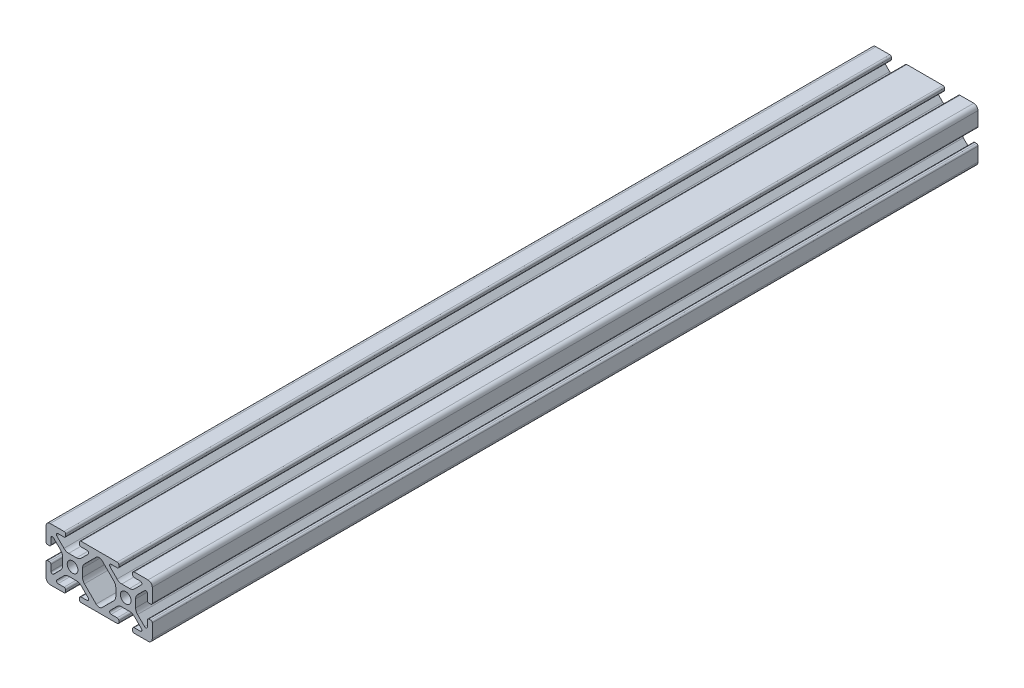
SolidWorks part; units mm, degrees
material "6063-T6"
ref_plane "Front" through (0, 0, 0) normal (0, 0, 1) x (1, 0, 0)
ref_plane "Top" through (0, 0, 0) normal (0, 1, 0) x (1, 0, 0)
ref_plane "Right" through (0, 0, 0) normal (1, 0, 0) x (0, 0, -1)
sketch "Sketch1" plane through (0, 0, 0) normal (0, 0, 1) x (1, 0, 0)
  line L0 (0, 0) -> (-63.6091, 63.6091) construction
  line L1 (0, 0) -> (53.0782, 0) construction
  line L2 (69.5504, 69.5504) -> (0, 0) construction
  line L3 (-7.4998, 9.0624) -> (-4.1172, 5.6797)
  line L4 (-10.668, 12.7) -> (10.668, 12.7) construction
  line L5 (-1.8721, 4.7498) -> (1.8721, 4.7498)
  line L6 (4.1172, 5.6797) -> (7.4998, 9.0624)
  line L7 (-3.302, 11.938) -> (-3.302, 11.1252)
  line L8 (-12.7, 10.668) -> (-12.7, -2.9469) construction
  line L9 (-10.668, 12.7) -> (-4.064, 12.7)
  line L10 (10.668, 12.7) -> (4.064, 12.7)
  line L11 (-6.961, 10.3632) -> (-4.064, 10.3632)
  line L12 (6.961, 10.3632) -> (4.064, 10.3632)
  line L13 (3.302, 11.938) -> (3.302, 11.1252)
  line L14 (-12.7, 10.668) -> (-12.7, 4.064)
  line L15 (-11.938, 3.302) -> (-11.1252, 3.302)
  line L16 (-10.3632, 4.064) -> (-10.3632, 6.961)
  line L17 (-9.0624, 7.4998) -> (-5.6797, 4.1172)
  line L18 (-4.7498, 1.8721) -> (-4.7498, -1.8721)
  line L19 (10.668, 12.7) -> (14.732, 12.7)
  line L20 (12.7, 12.7) -> (12.7, 19.2191) construction
  line L21 (4.7498, -1.8721) -> (4.7498, 1.8721)
  line L22 (5.6797, 4.1172) -> (11.2632, 9.7006)
  line L23 (5.6797, -4.1172) -> (11.2632, -9.7006)
  line L24 (10.668, -12.7) -> (14.732, -12.7)
  line L25 (-9.0624, -7.4998) -> (-5.6797, -4.1172)
  line L26 (-10.3632, -4.064) -> (-10.3632, -6.961)
  line L27 (-11.938, -3.302) -> (-11.1252, -3.302)
  line L28 (-12.7, -10.668) -> (-12.7, -4.064)
  line L29 (3.302, -11.938) -> (3.302, -11.1252)
  line L30 (6.961, -10.3632) -> (4.064, -10.3632)
  line L31 (-6.961, -10.3632) -> (-4.064, -10.3632)
  line L32 (10.668, -12.7) -> (4.064, -12.7)
  line L33 (-10.668, -12.7) -> (-4.064, -12.7)
  line L34 (-3.302, -11.938) -> (-3.302, -11.1252)
  line L35 (4.1172, -5.6797) -> (7.4998, -9.0624)
  line L36 (-1.8721, -4.7498) -> (1.8721, -4.7498)
  line L37 (-7.4998, -9.0624) -> (-4.1172, -5.6797)
  line L38 (32.8998, -9.0624) -> (29.5172, -5.6797)
  line L39 (27.2721, -4.7498) -> (23.5279, -4.7498)
  line L40 (21.2828, -5.6797) -> (17.9002, -9.0624)
  line L41 (28.702, -11.938) -> (28.702, -11.1252)
  line L42 (36.068, -12.7) -> (29.464, -12.7)
  line L43 (14.732, -12.7) -> (21.336, -12.7)
  line L44 (32.361, -10.3632) -> (29.464, -10.3632)
  line L45 (18.439, -10.3632) -> (21.336, -10.3632)
  line L46 (22.098, -11.938) -> (22.098, -11.1252)
  line L47 (38.1, -10.668) -> (38.1, -4.064)
  line L48 (37.338, -3.302) -> (36.5252, -3.302)
  line L49 (35.7632, -4.064) -> (35.7632, -6.961)
  line L50 (34.4624, -7.4998) -> (31.0797, -4.1172)
  line L51 (19.7203, -4.1172) -> (14.1368, -9.7006)
  line L52 (19.7203, 4.1172) -> (14.1368, 9.7006)
  line L53 (20.6502, -1.8721) -> (20.6502, 1.8721)
  line L54 (30.1498, 1.8721) -> (30.1498, -1.8721)
  line L55 (34.4624, 7.4998) -> (31.0797, 4.1172)
  line L56 (35.7632, 4.064) -> (35.7632, 6.961)
  line L57 (37.338, 3.302) -> (36.5252, 3.302)
  line L58 (38.1, 10.668) -> (38.1, 4.064)
  line L59 (22.098, 11.938) -> (22.098, 11.1252)
  line L60 (18.439, 10.3632) -> (21.336, 10.3632)
  line L61 (32.361, 10.3632) -> (29.464, 10.3632)
  line L62 (14.732, 12.7) -> (21.336, 12.7)
  line L63 (36.068, 12.7) -> (29.464, 12.7)
  line L64 (28.702, 11.938) -> (28.702, 11.1252)
  line L65 (21.2828, 5.6797) -> (17.9002, 9.0624)
  line L66 (27.2721, 4.7498) -> (23.5279, 4.7498)
  line L67 (32.8998, 9.0624) -> (29.5172, 5.6797)
  circle A0 centre (0, 0) radius 2.5527
  arc A1 (-10.668, 12.7) -> (-12.7, 10.668) centre (-10.668, 10.668) ccw
  arc A2 (14.1368, 9.7006) -> (11.2632, 9.7006) centre (12.7, 8.2638) ccw
  arc A3 (7.4998, 9.0624) -> (6.961, 10.3632) centre (6.961, 9.6012) ccw
  arc A4 (3.302, 11.1252) -> (4.064, 10.3632) centre (4.064, 11.1252) ccw
  arc A5 (3.302, 11.938) -> (4.064, 12.7) centre (4.064, 11.938) cw
  arc A6 (-3.302, 11.938) -> (-4.064, 12.7) centre (-4.064, 11.938) ccw
  arc A7 (-4.064, 10.3632) -> (-3.302, 11.1252) centre (-4.064, 11.1252) ccw
  arc A8 (-7.4998, 9.0624) -> (-6.961, 10.3632) centre (-6.961, 9.6012) cw
  arc A9 (1.8721, 4.7498) -> (4.1172, 5.6797) centre (1.8721, 7.9248) ccw
  arc A10 (-4.1172, 5.6797) -> (-1.8721, 4.7498) centre (-1.8721, 7.9248) ccw
  arc A11 (-5.6797, 4.1172) -> (-4.7498, 1.8721) centre (-7.9248, 1.8721) cw
  arc A12 (-12.7, 4.064) -> (-11.938, 3.302) centre (-11.938, 4.064) ccw
  arc A13 (-11.1252, 3.302) -> (-10.3632, 4.064) centre (-11.1252, 4.064) ccw
  arc A14 (-10.3632, 6.961) -> (-9.0624, 7.4998) centre (-9.6012, 6.961) cw
  arc A15 (4.7498, 1.8721) -> (5.6797, 4.1172) centre (7.9248, 1.8721) cw
  arc A16 (4.7498, -1.8721) -> (5.6797, -4.1172) centre (7.9248, -1.8721) ccw
  arc A17 (-10.3632, -6.961) -> (-9.0624, -7.4998) centre (-9.6012, -6.961) ccw
  arc A18 (-11.1252, -3.302) -> (-10.3632, -4.064) centre (-11.1252, -4.064) cw
  arc A19 (-12.7, -4.064) -> (-11.938, -3.302) centre (-11.938, -4.064) cw
  arc A20 (-5.6797, -4.1172) -> (-4.7498, -1.8721) centre (-7.9248, -1.8721) ccw
  arc A21 (-4.1172, -5.6797) -> (-1.8721, -4.7498) centre (-1.8721, -7.9248) cw
  arc A22 (1.8721, -4.7498) -> (4.1172, -5.6797) centre (1.8721, -7.9248) cw
  arc A23 (-7.4998, -9.0624) -> (-6.961, -10.3632) centre (-6.961, -9.6012) ccw
  arc A24 (-4.064, -10.3632) -> (-3.302, -11.1252) centre (-4.064, -11.1252) cw
  arc A25 (-3.302, -11.938) -> (-4.064, -12.7) centre (-4.064, -11.938) cw
  arc A26 (3.302, -11.938) -> (4.064, -12.7) centre (4.064, -11.938) ccw
  arc A27 (3.302, -11.1252) -> (4.064, -10.3632) centre (4.064, -11.1252) cw
  arc A28 (7.4998, -9.0624) -> (6.961, -10.3632) centre (6.961, -9.6012) cw
  arc A29 (14.1368, -9.7006) -> (11.2632, -9.7006) centre (12.7, -8.2638) cw
  arc A30 (-10.668, -12.7) -> (-12.7, -10.668) centre (-10.668, -10.668) cw
  arc A31 (36.068, -12.7) -> (38.1, -10.668) centre (36.068, -10.668) ccw
  arc A32 (17.9002, -9.0624) -> (18.439, -10.3632) centre (18.439, -9.6012) ccw
  arc A33 (22.098, -11.1252) -> (21.336, -10.3632) centre (21.336, -11.1252) ccw
  arc A34 (22.098, -11.938) -> (21.336, -12.7) centre (21.336, -11.938) cw
  arc A35 (28.702, -11.938) -> (29.464, -12.7) centre (29.464, -11.938) ccw
  arc A36 (29.464, -10.3632) -> (28.702, -11.1252) centre (29.464, -11.1252) ccw
  arc A37 (32.8998, -9.0624) -> (32.361, -10.3632) centre (32.361, -9.6012) cw
  arc A38 (23.5279, -4.7498) -> (21.2828, -5.6797) centre (23.5279, -7.9248) ccw
  arc A39 (29.5172, -5.6797) -> (27.2721, -4.7498) centre (27.2721, -7.9248) ccw
  arc A40 (31.0797, -4.1172) -> (30.1498, -1.8721) centre (33.3248, -1.8721) cw
  arc A41 (38.1, -4.064) -> (37.338, -3.302) centre (37.338, -4.064) ccw
  arc A42 (36.5252, -3.302) -> (35.7632, -4.064) centre (36.5252, -4.064) ccw
  arc A43 (35.7632, -6.961) -> (34.4624, -7.4998) centre (35.0012, -6.961) cw
  arc A44 (20.6502, -1.8721) -> (19.7203, -4.1172) centre (17.4752, -1.8721) cw
  arc A45 (20.6502, 1.8721) -> (19.7203, 4.1172) centre (17.4752, 1.8721) ccw
  arc A46 (35.7632, 6.961) -> (34.4624, 7.4998) centre (35.0012, 6.961) ccw
  arc A47 (36.5252, 3.302) -> (35.7632, 4.064) centre (36.5252, 4.064) cw
  arc A48 (38.1, 4.064) -> (37.338, 3.302) centre (37.338, 4.064) cw
  arc A49 (31.0797, 4.1172) -> (30.1498, 1.8721) centre (33.3248, 1.8721) ccw
  arc A50 (29.5172, 5.6797) -> (27.2721, 4.7498) centre (27.2721, 7.9248) cw
  arc A51 (23.5279, 4.7498) -> (21.2828, 5.6797) centre (23.5279, 7.9248) cw
  arc A52 (32.8998, 9.0624) -> (32.361, 10.3632) centre (32.361, 9.6012) ccw
  arc A53 (29.464, 10.3632) -> (28.702, 11.1252) centre (29.464, 11.1252) cw
  arc A54 (28.702, 11.938) -> (29.464, 12.7) centre (29.464, 11.938) cw
  arc A55 (22.098, 11.938) -> (21.336, 12.7) centre (21.336, 11.938) ccw
  arc A56 (22.098, 11.1252) -> (21.336, 10.3632) centre (21.336, 11.1252) cw
  arc A57 (17.9002, 9.0624) -> (18.439, 10.3632) centre (18.439, 9.6012) cw
  arc A58 (36.068, 12.7) -> (38.1, 10.668) centre (36.068, 10.668) cw
  circle A59 centre (25.4, 0) radius 2.5527
  point P21 (-12.7, 12.7)
  point P22 (12.7, 12.7)
  point P41 (-12.7, -12.7)
  point P49 (4.7498, 0)
  point P50 (30.1498, 0)
  point P106 (-4.7498, 0)
  point P195 (12.7, -12.7)
  point P196 (12.7, 12.7)
  point P197 (20.6502, 0)
  point P198 (38.1, -12.7)
  point P199 (38.1, 12.7)
  dimension "D3" = 5.1054
  dimension "D5" = 2.032
  dimension "D13" = 0.762
  dimension "D15" = 3.175
  dimension "D22" = 3.175
  dimension "D23" = 0.762
  dimension "D27" = 2.032
  dimension "D28" = 3.175
  dimension "D14" = 5.6134
  dimension "D19" = 5.6134
  dimension "D1" = 45
  dimension "D2" = 90
  dimension "D4" = 12.7
  dimension "D6" = 2.2098
  dimension "D7" = 2.2098
  dimension "D8" = 6.604
  dimension "D9" = 9.398
  dimension "D10" = 0
  dimension "D11" = 0
  dimension "D12" = 7.9502
  dimension "D16" = 0
  dimension "D17" = 0
  dimension "D18" = 7.9502
  dimension "D20" = 2.2098
  dimension "D21" = 9.398
  dimension "D24" = 7.366
  dimension "D25" = 2.2098
  dimension "D26" = 7.9502
  dimension "D29" = 50.8
  dimension "D30" = 25.4
extrude "Boss-Extrude1" add sketch "Sketch1" along normal blind 394.716
sketch "Sketch2" plane through (0, 0, 0) normal (0, 0, 1) x (1, 0, 0)
  line L0 (-7.3202, 8.8828) -> (-7.3202, 8.5236)
  line L1 (-7.3202, 8.5236) -> (-6.961, 8.5236)
  line L2 (-6.961, 8.5236) -> (-7.3202, 8.8828)
  line L3 (-4.1172, 5.6797) -> (-7.4998, 9.0624) construction
  dimension "D1" = 0.254
  dimension "D2" = 0.254
extrude "Cut-Extrude2" [suppressed] cut sketch "Sketch2" along normal through all
